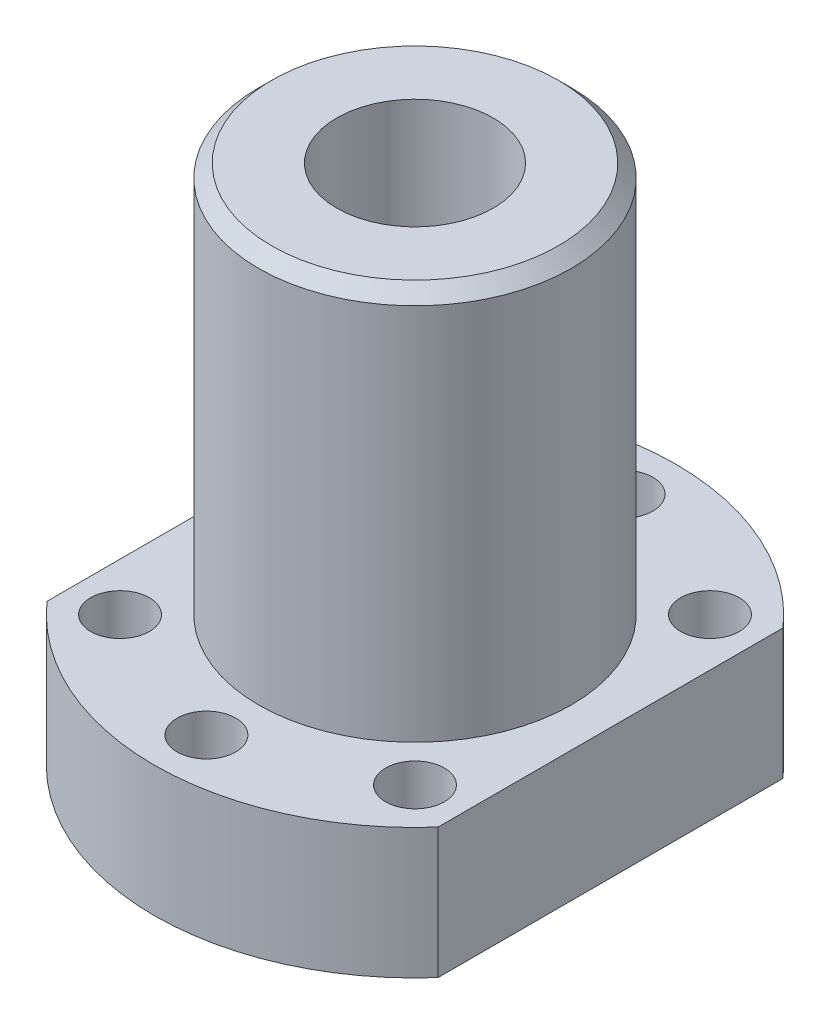
SolidWorks part; units mm, degrees
ref_plane "Front" through (0, 0, 0) normal (0, 0, 1) x (1, 0, 0)
ref_plane "Top" through (0, 0, 0) normal (0, 1, 0) x (1, 0, 0)
ref_plane "Right" through (0, 0, 0) normal (1, 0, 0) x (0, 0, -1)
sketch "草图1" plane through (0, 0, 0) normal (0, 1, 0) x (1, 0, 0)
  line L0 (-33.7029, 0) -> (40.1439, 0) construction
  line L1 (0, 28.4018) -> (0, -27.3268) construction
  line L2 (-15, 13.2288) -> (-15, -13.2288)
  line L3 (15, 13.2288) -> (15, -13.2288)
  line L4 (0, 0) -> (19.4435, 19.4435) construction
  circle A0 centre (0, 0) radius 20 construction
  arc A1 (-15, 13.2288) -> (15, 13.2288) centre (0, 0) cw
  arc A2 (-15, -13.2288) -> (15, -13.2288) centre (0, 0) ccw
  circle A3 centre (0, 0) radius 6
  circle A4 centre (0, 16) radius 2.25
  circle A5 centre (11.3137, 11.3137) radius 2.25
  circle A6 centre (-11.3137, 11.3137) radius 2.25
  circle A7 centre (-11.3137, -11.3137) radius 2.25
  circle A8 centre (0, -16) radius 2.25
  circle A9 centre (11.3137, -11.3137) radius 2.25
  point P18 (0, 0)
  dimension "D1" = 40
  dimension "D3" = 12
  dimension "D4" = 4.5
  dimension "D2" = 30
  dimension "D5" = 16
  dimension "D6" = 2
extrude "凸台-拉伸1" add sketch "草图1" along normal blind 10
sketch "草图2" plane through (0, 10, 0) normal (0, 1, 0) x (1, 0, 0)
  circle A0 centre (0, 0) radius 6
  circle A1 centre (0, 0) radius 12
  dimension "D1" = 24
extrude "凸台-拉伸2" add sketch "草图2" along normal blind 30
chamfer "倒角1" distance 1 angle 45 1 edges at (0, 40, 12)
